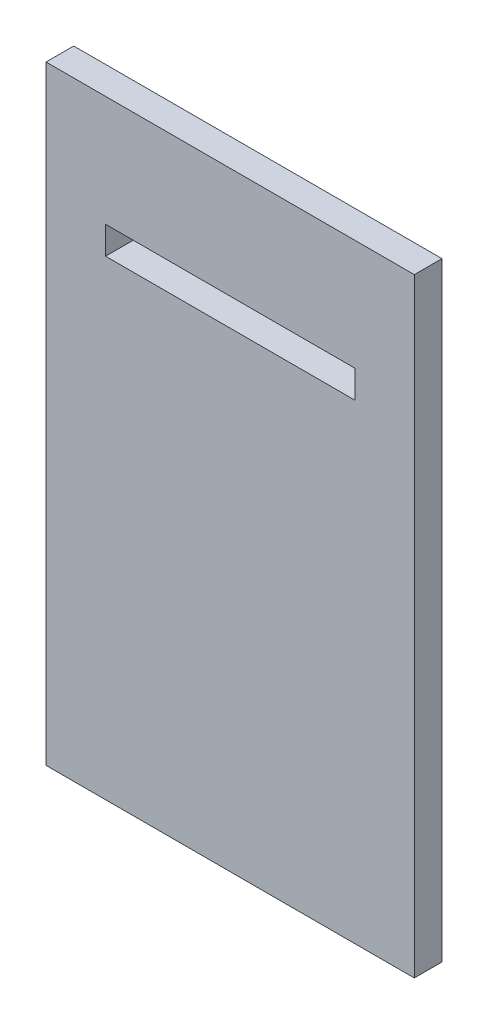
SolidWorks part; units mm, degrees
ref_plane "Plan de face" through (0, 0, 0) normal (0, 0, 1) x (1, 0, 0)
ref_plane "Plan de dessus" through (0, 0, 0) normal (0, 1, 0) x (1, 0, 0)
ref_plane "Plan de droite" through (0, 0, 0) normal (1, 0, 0) x (0, 0, -1)
sketch "Esquisse1" plane through (0, 0, 0) normal (0, 0, 1) x (1, 0, 0)
  line L0 (0, 220) -> (133, 220)
  line L1 (0, 0) -> (133, 0)
  line L2 (0, 0) -> (0, 220)
  line L3 (0, 180) -> (133, 180) construction
  line L4 (133, 0) -> (133, 220)
  line L5 (133, 175) -> (0, 175) construction
  line L6 (0, 170) -> (133, 170) construction
  line L7 (111.5, 170) -> (21.5, 170) construction
  line L8 (21.5, 180) -> (111.5, 180)
  line L9 (111.5, 170) -> (21.5, 170)
  line L11 (21.5, 180) -> (21.5, 170)
  line L13 (111.5, 180) -> (111.5, 170)
  line L16 (66.5, 170) -> (66.5, 180) construction
  dimension "D1" = 10
  dimension "D2" = 5
  dimension "D3" = 40
  dimension "D4" = 220
  dimension "D5" = 133
  dimension "D7" = 90
extrude "Boss.-Extru.1" add sketch "Esquisse1" along normal blind 10
